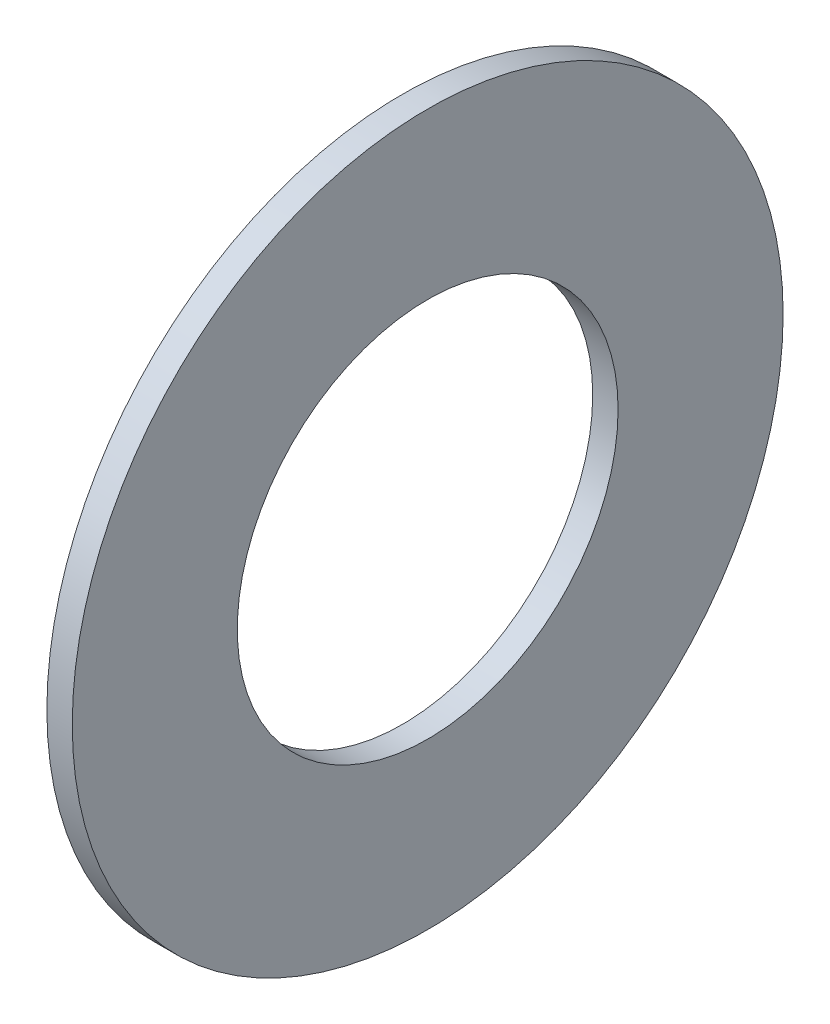
SolidWorks part; units mm, degrees
material "Chrome Stainless Steel"
ref_plane "Front Plane" through (0, 0, 0) normal (0, 0, 1) x (1, 0, 0)
ref_plane "Top Plane" through (0, 0, 0) normal (0, 1, 0) x (1, 0, 0)
ref_plane "Right Plane" through (0, 0, 0) normal (1, 0, 0) x (0, 0, -1)
sketch "Sketch1" plane through (0, 0, 0) normal (1, 0, 0) x (0, 0, -1)
  circle A0 centre (0, 0) radius 14
  circle A1 centre (0, 0) radius 7.5
  dimension "OD" = 28
  dimension "Shaft Dia" = 15
extrude "Extrude1" add sketch "Sketch1" along normal blind 1
